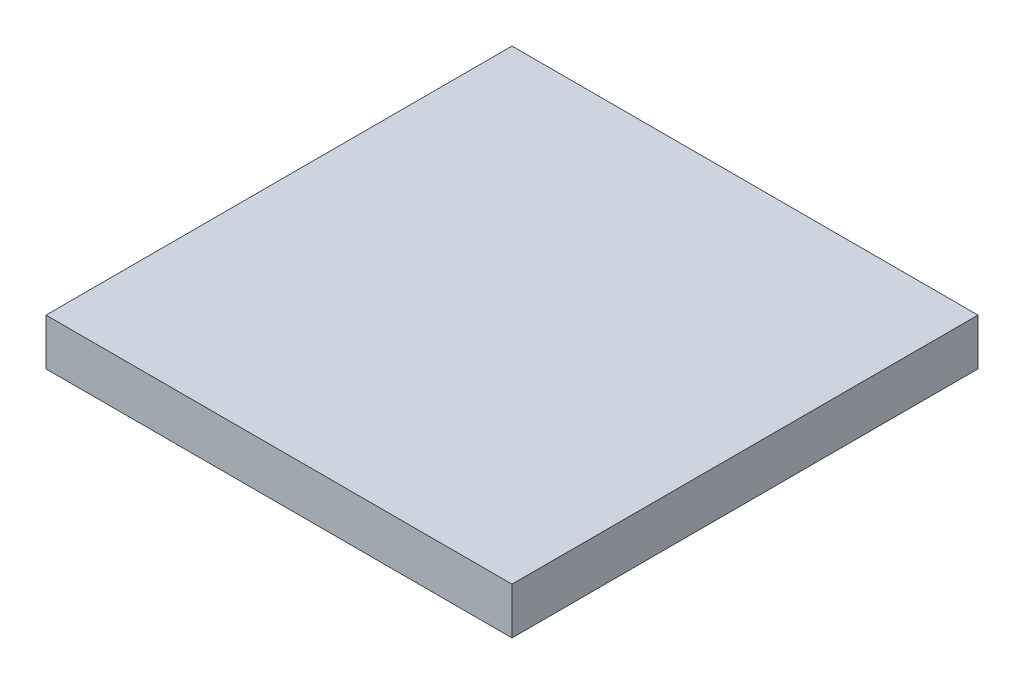
SolidWorks part; units mm, degrees
ref_plane "Front Plane" through (0, 0, 0) normal (0, 0, 1) x (1, 0, 0)
ref_plane "Top Plane" through (0, 0, 0) normal (0, 1, 0) x (1, 0, 0)
ref_plane "Right Plane" through (0, 0, 0) normal (1, 0, 0) x (0, 0, -1)
sketch "Sketch1" plane through (0, 0, 0) normal (0, 1, 0) x (1, 0, 0)
  line L1 (-46.3511, 218.3473) -> (153.6489, 218.3473)
  line L2 (-46.3511, 218.3473) -> (-46.3511, 18.3473)
  line L3 (-46.3511, 18.3473) -> (153.6489, 18.3473)
  line L4 (153.6489, 218.3473) -> (153.6489, 18.3473)
extrude "Boss-Extrude1" add sketch "Sketch1" along normal blind 20
